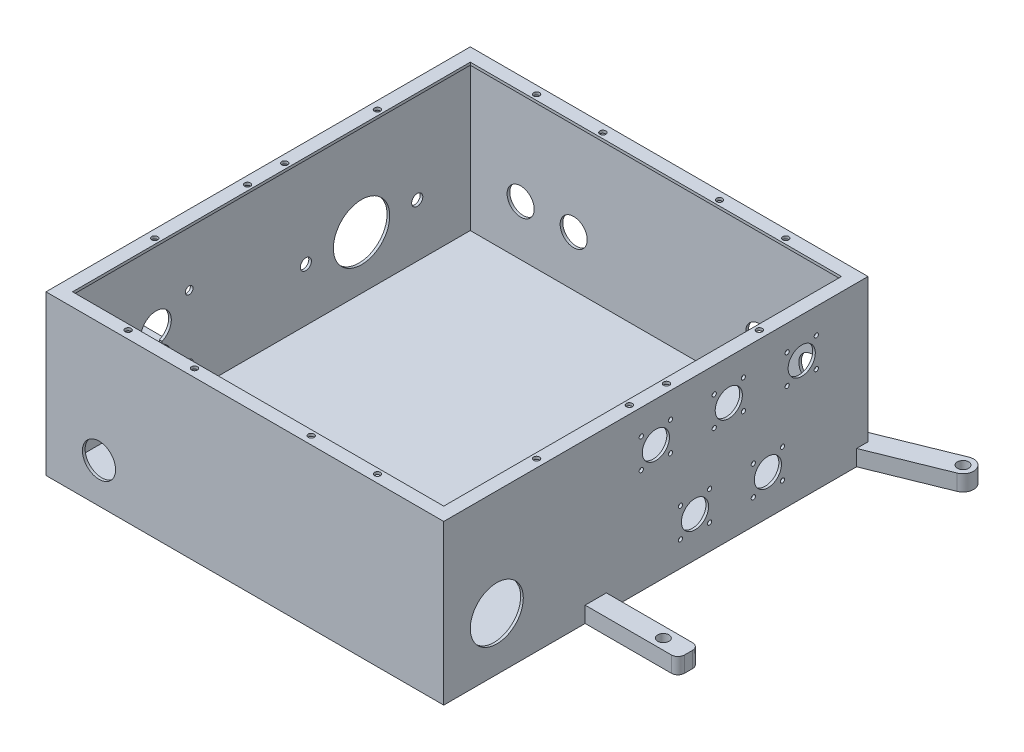
SolidWorks part; units mm, degrees
ref_plane "Front Plane" through (0, 0, 0) normal (0, 0, 1) x (1, 0, 0)
ref_plane "Top Plane" through (0, 0, 0) normal (0, 1, 0) x (1, 0, 0)
ref_plane "Right Plane" through (0, 0, 0) normal (1, 0, 0) x (0, 0, -1)
sketch "Sketch3" plane through (0, 0, 0) normal (0, 1, 0) x (1, 0, 0)
  line L1 (-150, -160) -> (150, -160)
  line L2 (-150, -160) -> (-150, 160)
  line L3 (-150, 160) -> (150, 160)
  line L4 (150, -160) -> (150, 160)
  line L5 (-150, -160) -> (150, 160) construction
  line L6 (-150, 160) -> (150, -160) construction
  point P0 (0, 0)
  dimension "D1" = 300
  dimension "D2" = 320
extrude "Boss-Extrude3" add sketch "Sketch3" along normal blind 2
sketch "Sketch4" plane through (0, 0, 0) normal (0, 1, 0) x (1, 0, 0)
  line L0 (-148, -158) -> (-148, 158)
  line L1 (-150, -160) -> (150, -160)
  line L2 (-150, -160) -> (-150, 160)
  line L3 (-150, 160) -> (150, 160)
  line L4 (150, -160) -> (150, 160)
  line L5 (-150, -160) -> (150, 160) construction
  line L6 (-150, 160) -> (150, -160) construction
  line L7 (-148, 158) -> (148, 158)
  line L8 (148, -158) -> (148, 158)
  line L9 (-148, -158) -> (148, -158)
  point P0 (0, 0)
  dimension "D1" = 2
extrude "Boss-Extrude4" add sketch "Sketch4" along normal blind 120
sketch "Sketch5" plane through (0, 0, -160) normal (0, 0, -1) x (-1, 0, 0)
  line L0 (-150, 120) -> (-150, 0) construction
  line L1 (-150, 0) -> (150, 0) construction
  line L2 (150, 120) -> (150, 0) construction
  circle A0 centre (-110, 40) radius 10.2
  circle A1 centre (-70, 40) radius 10.2
  circle A2 centre (70, 40) radius 10.2
  circle A3 centre (110, 40) radius 10.2
  dimension "D1" = 20.4
  dimension "D2" = 20.4
  dimension "D3" = 20.4
  dimension "D4" = 20.4
  dimension "D5" = 40
  dimension "D6" = 40
  dimension "D7" = 40
  dimension "D8" = 40
  dimension "D9" = 40
extrude "Cut-Extrude1" cut sketch "Sketch5" against normal blind 120
sketch "Sketch6" plane through (0, 0, 160) normal (0, 0, 1) x (1, 0, 0)
  line L0 (-150, 120) -> (-150, 0) construction
  line L1 (-150, 0) -> (150, 0) construction
  circle A0 centre (-110, 30) radius 12.5
  dimension "D1" = 25
  dimension "D2" = 40
  dimension "D3" = 30
extrude "Cut-Extrude2" cut sketch "Sketch6" against normal blind 120
sketch "Sketch7" plane through (-150, 0, 0) normal (-1, 0, 0) x (0, 0, 1)
  line L0 (160, 120) -> (160, 0) construction
  line L1 (-160, 120) -> (-160, 0) construction
  line L2 (-160, 0) -> (160, 0) construction
  line L3 (93.7, 40.25) -> (88.3106, 40.25)
  line L4 (93.7, 40.25) -> (93.7, 49.75)
  line L5 (93.7, 49.75) -> (88.3106, 49.75)
  line L6 (74.5, 44.083) -> (74.5, 45.917)
  line L7 (48, 15) -> (110, 15)
  line L8 (48, 15) -> (48, 75)
  line L9 (48, 75) -> (110, 75)
  line L10 (110, 15) -> (110, 75)
  circle A0 centre (-76, 42) radius 21.25
  circle A1 centre (-34, 42) radius 4.2
  circle A2 centre (-118, 42) radius 4.2
  arc A3 (88.3106, 49.75) -> (74.5, 45.917) centre (79, 56.5) ccw
  arc A4 (74.5, 44.083) -> (88.3106, 40.25) centre (79, 33.5) ccw
  circle A5 centre (54, 69) radius 2.9
  circle A6 centre (104, 69) radius 2.9
  circle A7 centre (54, 21) radius 2.9
  circle A8 centre (104, 21) radius 2.9
  point P18 (74.5, 45)
  dimension "D1" = 42.5
  dimension "D2" = 8.4
  dimension "D3" = 8.4
  dimension "D8" = 23
  dimension "D9" = 23
  dimension "D18" = 5.8
  dimension "D26" = 50
  dimension "D27" = 5.8
  dimension "D4" = 42
  dimension "D5" = 42
  dimension "D6" = 42
  dimension "D7" = 42
  dimension "D10" = 23
  dimension "D11" = 14.7
  dimension "D12" = 4.5
  dimension "D13" = 4.75
  dimension "D14" = 11.5
  dimension "D15" = 60
  dimension "D16" = 9.5
  dimension "D17" = 62
  dimension "D19" = 6
  dimension "D20" = 6
  dimension "D21" = 18.5
  dimension "D22" = 31
  dimension "D23" = 50
  dimension "D24" = 15
  dimension "D28" = 6
  dimension "D29" = 6
  dimension "D31" = 50
  dimension "D25" = 2
  dimension "D30" = 2
extrude "Cut-Extrude4" cut sketch "Sketch7" against normal blind 18.5 contours A6 | A5 | L6 A3 L5 L4 L3 A4 | A7 | A8 | A0 | A2 | A1
sketch "Sketch8" plane through (150, 0, 0) normal (1, 0, 0) x (0, 0, -1)
  line L0 (15, 44.5) -> (44, 44.5) construction
  line L1 (15, 44.5) -> (15, 15.5) construction
  line L2 (15, 15.5) -> (44, 15.5) construction
  line L3 (-160, 120) -> (160, 120) construction
  line L12 (95.5, 75.5) -> (124.5, 75.5) construction
  line L13 (95.5, 75.5) -> (95.5, 104.5) construction
  line L14 (95.5, 104.5) -> (124.5, 104.5) construction
  line L15 (124.5, 75.5) -> (124.5, 104.5) construction
  line L16 (160, 120) -> (160, 0) construction
  line L17 (40.5, 75.5) -> (69.5, 75.5) construction
  line L18 (40.5, 75.5) -> (40.5, 104.5) construction
  line L19 (40.5, 104.5) -> (69.5, 104.5) construction
  line L20 (69.5, 75.5) -> (69.5, 104.5) construction
  line L21 (-14.5, 75.5) -> (14.5, 75.5) construction
  line L22 (-14.5, 75.5) -> (-14.5, 104.5) construction
  line L23 (-14.5, 104.5) -> (14.5, 104.5) construction
  line L24 (14.5, 75.5) -> (14.5, 104.5) construction
  line L25 (-160, 0) -> (160, 0) construction
  line L26 (70, 44.5) -> (99, 44.5) construction
  line L27 (70, 44.5) -> (70, 15.5) construction
  line L28 (70, 15.5) -> (99, 15.5) construction
  line L29 (99, 44.5) -> (99, 15.5) construction
  line L30 (44, 44.5) -> (44, 15.5) construction
  line L31 (-160, 120) -> (-160, 0) construction
  circle A5 centre (110, 90) radius 10.25
  circle A6 centre (121, 101) radius 1.6
  circle A7 centre (99, 101) radius 1.6
  circle A8 centre (121, 79) radius 1.6
  circle A9 centre (99, 79) radius 1.6
  circle A10 centre (55, 90) radius 10.25
  circle A11 centre (66, 101) radius 1.6
  circle A12 centre (44, 101) radius 1.6
  circle A13 centre (66, 79) radius 1.6
  circle A14 centre (44, 79) radius 1.6
  circle A15 centre (0, 90) radius 10.25
  circle A16 centre (11, 101) radius 1.6
  circle A17 centre (-11, 101) radius 1.6
  circle A18 centre (11, 79) radius 1.6
  circle A19 centre (-11, 79) radius 1.6
  circle A20 centre (84.5, 30) radius 10.25
  circle A21 centre (95.5, 41) radius 1.6
  circle A22 centre (95.5, 19) radius 1.6
  circle A23 centre (73.5, 41) radius 1.6
  circle A24 centre (73.5, 19) radius 1.6
  circle A25 centre (29.5, 30) radius 10.25
  circle A26 centre (40.5, 41) radius 1.6
  circle A27 centre (40.5, 19) radius 1.6
  circle A28 centre (18.5, 41) radius 1.6
  circle A29 centre (18.5, 19) radius 1.6
  circle A30 centre (-120, 40) radius 20
  dimension "D1" = 20.5
  dimension "D2" = 29
  dimension "D6" = 3.2
  dimension "D7" = 11
  dimension "D8" = 2
  dimension "D14" = 30
  dimension "D15" = 50
  dimension "D9" = 3.2
  dimension "D22" = 20.5
  dimension "D23" = 3.2
  dimension "D24" = 3.2
  dimension "D37" = 40
  dimension "D3" = 29
  dimension "D4" = 14.5
  dimension "D5" = 14.5
  dimension "D10" = 22
  dimension "D11" = 22
  dimension "D12" = 2
  dimension "D13" = 22
  dimension "D16" = 11
  dimension "D17" = 11
  dimension "D19" = 55
  dimension "D20" = 29
  dimension "D21" = 29
  dimension "D25" = 14.5
  dimension "D26" = 14.5
  dimension "D27" = 11
  dimension "D28" = 22
  dimension "D29" = 11
  dimension "D30" = 30
  dimension "D31" = 75.5
  dimension "D32" = 11
  dimension "D34" = 22
  dimension "D36" = 55
  dimension "D38" = 40
  dimension "D39" = 40
  dimension "D18" = 3
  dimension "D33" = 2
  dimension "D35" = 2
extrude "Cut-Extrude5" cut sketch "Sketch8" against normal blind 10
ref_plane "Plane1" through (0, 120, 0) normal (0, 1, 0) x (1, 0, 0)
sketch "Sketch10" plane through (0, 120, 0) normal (0, 1, 0) x (1, 0, 0)
  line L0 (-148, -158) -> (148, -158) construction
  line L1 (-148, 158) -> (-148, -158) construction
  line L2 (148, -158) -> (148, 158) construction
  line L3 (148, 158) -> (-148, 158) construction
  line L4 (-148, -158) -> (148, -158)
  line L5 (-148, 158) -> (-148, -158)
  line L6 (148, -158) -> (148, 158)
  line L7 (148, 158) -> (-148, 158)
  line L8 (-140, 150) -> (-140, -150)
  line L9 (-140, -150) -> (140, -150)
  line L10 (140, -150) -> (140, 150)
  line L11 (140, 150) -> (-140, 150)
  line L13 (0, -66) -> (0, 66) construction
  line L14 (-66, 0) -> (66, 0) construction
  circle A2 centre (-94, 154) radius 2.25
  circle A3 centre (-44, 154) radius 2.25
  circle A4 centre (-144, 84) radius 2.25
  circle A5 centre (-144, 14) radius 2.25
  circle A6 centre (144, 14) radius 2.25
  circle A7 centre (144, 84) radius 2.25
  circle A8 centre (44, 154) radius 2.25
  circle A9 centre (94, 154) radius 2.25
  circle A12 centre (94, -154) radius 2.25
  circle A13 centre (44, -154) radius 2.25
  circle A14 centre (144, -84) radius 2.25
  circle A15 centre (144, -14) radius 2.25
  circle A16 centre (-144, -14) radius 2.25
  circle A17 centre (-144, -84) radius 2.25
  circle A18 centre (-44, -154) radius 2.25
  circle A19 centre (-94, -154) radius 2.25
  dimension "D2" = 50
  dimension "D4" = 4.5
  dimension "D5" = 4.5
  dimension "D6" = 54
  dimension "D11" = 4.5
  dimension "D12" = 4.5
  dimension "D3" = 70
  dimension "D8" = 28
  dimension "D7" = 74
  dimension "D9" = 288
  dimension "D10" = 308
  dimension "D1" = 8
extrude "Boss-Extrude5" add sketch "Sketch10" against normal blind 2
sketch "Sketch11" plane through (0, 0, 0) normal (0, 1, 0) x (1, 0, 0)
  line L0 (-150, 160) -> (-150, -160) construction
  line L1 (-150, 130) -> (-170, 130)
  line L2 (-150, 130) -> (-150, 115)
  line L3 (-150, 115) -> (-170, 115)
  line L4 (-175, 125) -> (-175, 120)
  circle A0 centre (-165, 122.5) radius 4.2
  arc A1 (-170, 115) -> (-175, 120) centre (-170, 120) cw
  arc A2 (-175, 125) -> (-170, 130) centre (-170, 125) cw
  point P10 (-175, 115)
  point P13 (-175, 130)
  dimension "D3" = 8.4
  dimension "D5" = 5
  dimension "D1" = 25
  dimension "D2" = 15
  dimension "D4" = 10
  dimension "D6" = 30
  dimension "D7" = 7.5
extrude "Boss-Extrude6" [suppressed] add sketch "Sketch11" along normal blind 7
pattern_linear "LPattern1" [suppressed] count 2 spacing 80
mirror "Mirror1" [suppressed] about plane through (0, 0, 0) normal (1, 0, 0)
sketch "Sketch12" plane through (0, 0, 0) normal (0, 1, 0) x (1, 0, 0)
  line L0 (150, 160) -> (150, -45.35) construction
  line L1 (150, -160) -> (150, 160) construction
  line L2 (220, -45.35) -> (150, -45.35) construction
  line L3 (0, -66) -> (0, 66) construction
  line L4 (150, -37.35) -> (215, -37.35)
  line L5 (150, -37.35) -> (150, -53.35)
  line L6 (150, -53.35) -> (215, -53.35)
  line L7 (220, -42.35) -> (220, -48.35)
  line L8 (-220, -45.35) -> (-150, -45.35) construction
  line L9 (-220, -42.35) -> (-220, -48.35)
  line L10 (-150, -53.35) -> (-215, -53.35)
  line L11 (-150, -37.35) -> (-150, -53.35)
  line L12 (-150, -37.35) -> (-215, -37.35)
  circle A0 centre (201, -45.35) radius 4.25
  arc A1 (215, -53.35) -> (220, -48.35) centre (215, -48.35) ccw
  arc A2 (215, -37.35) -> (220, -42.35) centre (215, -42.35) cw
  arc A3 (-215, -37.35) -> (-220, -42.35) centre (-215, -42.35) ccw
  arc A4 (-215, -53.35) -> (-220, -48.35) centre (-215, -48.35) cw
  circle A5 centre (-201, -45.35) radius 4.25
  point P14 (220, -53.35)
  point P32 (0, 0)
  dimension "D5" = 8.5
  dimension "D7" = 5
  dimension "D1" = 205.35
  dimension "D2" = 8
  dimension "D3" = 51
  dimension "D4" = 70
  dimension "D6" = 8
extrude "Boss-Extrude7" add sketch "Sketch12" along normal blind 12
sketch "Sketch14" plane through (0, 0, 0) normal (0, 1, 0) x (1, 0, 0)
  line L0 (150, 160) -> (201, 180.65) construction
  line L1 (128.684, 160) -> (197.9976, 188.0652)
  line L2 (150, 151.3691) -> (204.0024, 173.2348)
  line L3 (146.9976, 167.4152) -> (197.9976, 188.0652) construction
  line L4 (150, 160) -> (-150, 160) construction
  line L5 (153.0024, 152.5848) -> (204.0024, 173.2348) construction
  line L6 (150, -160) -> (150, 160) construction
  line L7 (128.684, 160) -> (150, 160)
  line L8 (150, 160) -> (150, 151.3691)
  line L9 (0, -66) -> (0, 66) construction
  line L10 (-128.684, 160) -> (-150, 160)
  line L11 (-128.684, 160) -> (-197.9976, 188.0652)
  line L12 (-150, 160) -> (-201, 180.65) construction
  line L13 (-150, 151.3691) -> (-204.0024, 173.2348)
  line L14 (-150, 160) -> (-150, 151.3691)
  circle A0 centre (201, 180.65) radius 4.25
  arc A1 (197.9976, 188.0652) -> (204.0024, 173.2348) centre (201, 180.65) cw
  arc A2 (-197.9976, 188.0652) -> (-204.0024, 173.2348) centre (-201, 180.65) ccw
  circle A3 centre (-201, 180.65) radius 4.25
  dimension "D5" = 8.5
  dimension "D1" = 51
  dimension "D2" = 20.65
  dimension "D4" = 8
extrude "Boss-Extrude8" add sketch "Sketch14" along normal blind 12 separate body
